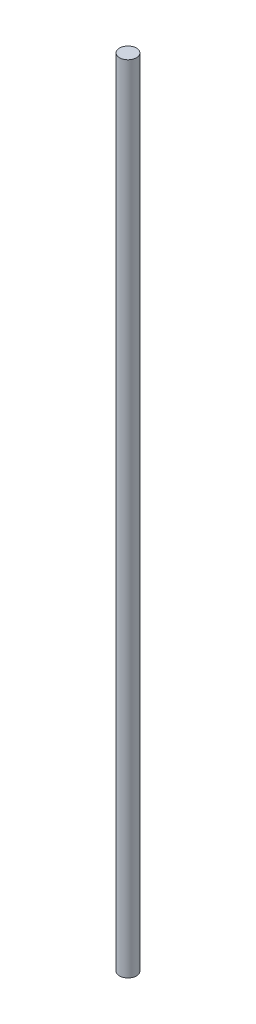
SolidWorks part; units mm, degrees
ref_plane "Front Plane" through (0, 0, 0) normal (0, 0, 1) x (1, 0, 0)
ref_plane "Top Plane" through (0, 0, 0) normal (0, 1, 0) x (1, 0, 0)
ref_plane "Right Plane" through (0, 0, 0) normal (1, 0, 0) x (0, 0, -1)
sketch "Sketch1" plane through (0, 0, 0) normal (0, 1, 0) x (1, 0, 0)
  circle A0 centre (0, 0) radius 4
  dimension "D1" = 8
extrude "Boss-Extrude1" add sketch "Sketch1" along normal blind 377 contours A0
